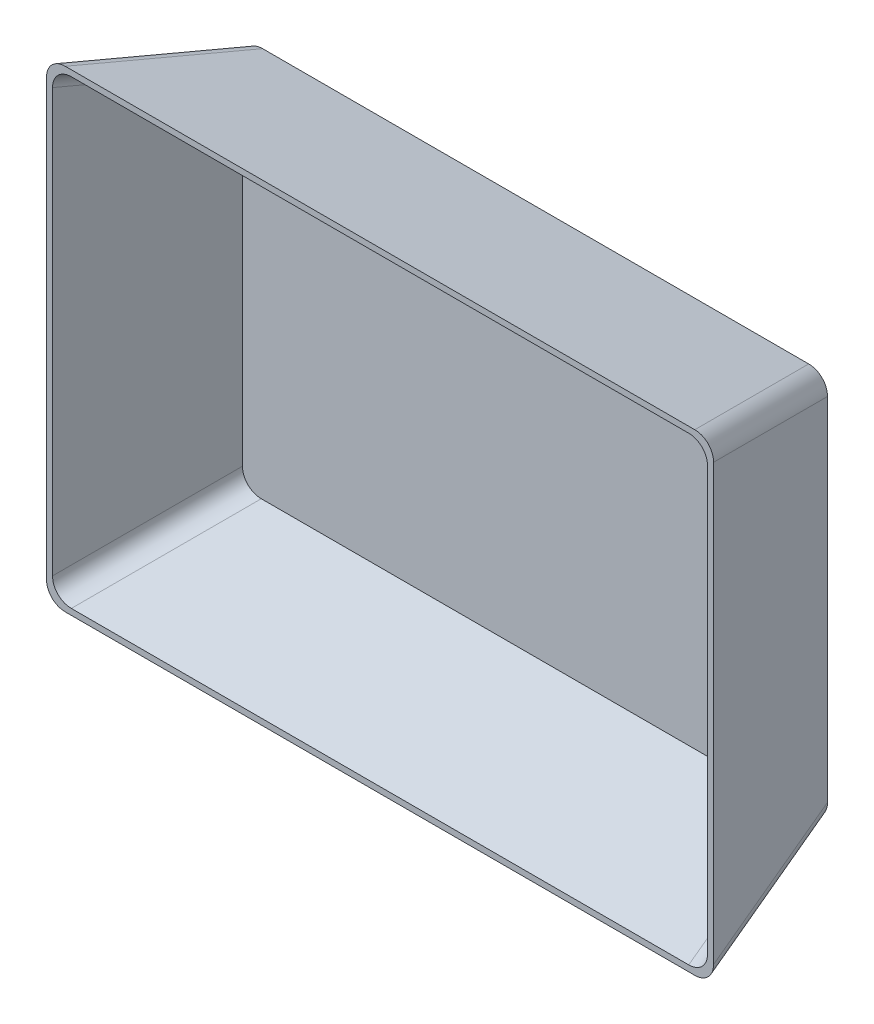
SolidWorks part; units mm, degrees
ref_plane "前视基准面" through (0, 0, 0) normal (0, 0, 1) x (1, 0, 0)
ref_plane "上视基准面" through (0, 0, 0) normal (0, 1, 0) x (1, 0, 0)
ref_plane "右视基准面" through (0, 0, 0) normal (1, 0, 0) x (0, 0, -1)
sketch "草图1" plane through (0, 0, 0) normal (0, 0, 1) x (1, 0, 0)
  line L1 (-150, -100) -> (150, -100)
  line L2 (-150, -100) -> (-150, 100)
  line L3 (-150, 100) -> (150, 100)
  line L4 (150, -100) -> (150, 100)
  line L5 (-150, -100) -> (150, 100) construction
  line L6 (-150, 100) -> (150, -100) construction
  point P0 (0, 0)
  dimension "D1" = 300
  dimension "D2" = 200
extrude "凸台-拉伸1" add sketch "草图1" along normal blind 80 draft 15 draft outward yes
shell "抽壳1" thickness 3
fillet "圆角1" radius 10 8 edges at (158.0141, 108.0141, 41.5) (-158.0141, -108.0141, 41.5) (158.0141, -108.0141, 41.5) (-158.0141, 108.0141, 41.5) (160.718, -110.718, 40) (-160.718, 110.718, 40) (160.718, 110.718, 40) (-160.718, -110.718, 40)
